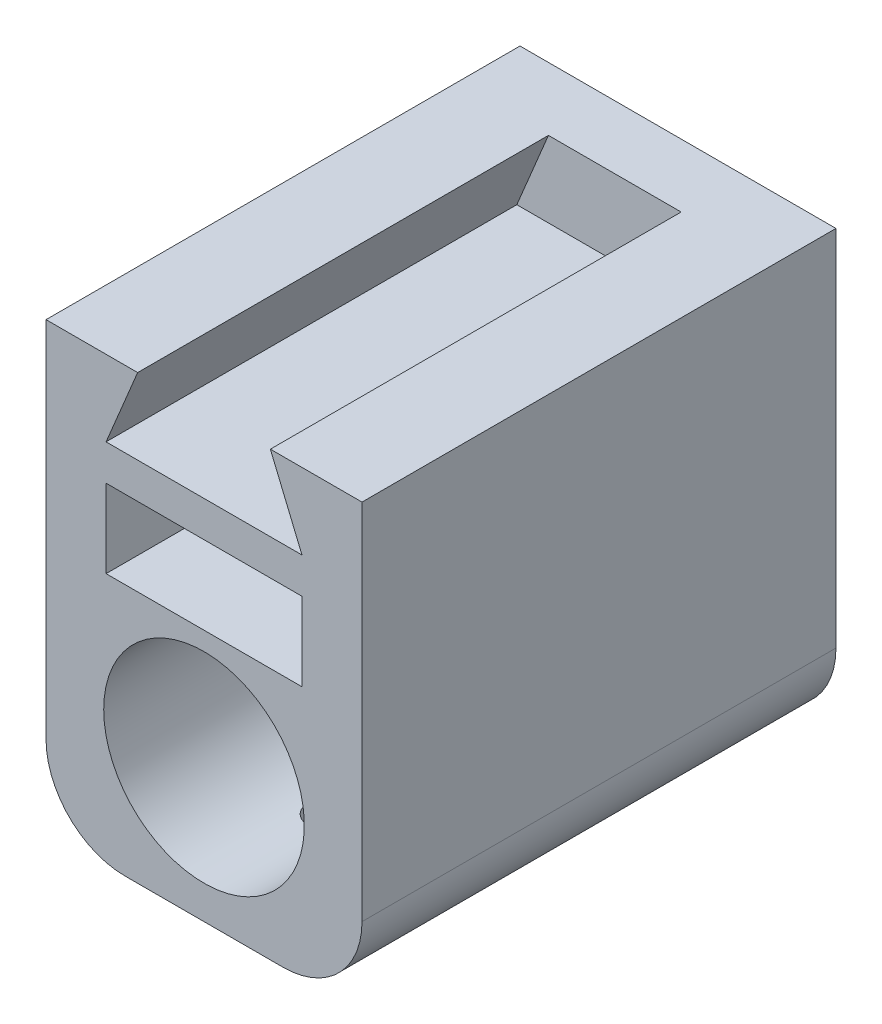
SolidWorks part; units mm, degrees
ref_plane "Plano frontal" through (0, 0, 0) normal (1, 0, 0) x (0, 1, 0)
ref_plane "Plano superior" through (0, 0, 0) normal (0, 0, 1) x (0, 1, 0)
ref_plane "Plano direito" through (0, 0, 0) normal (0, 1, 0) x (-1, 0, 0)
sketch "Esboço1" plane through (0, 0, 0) normal (0, 0, 1) x (0, 1, 0)
  line L16 (3.6178, 6.2) -> (3.6178, -6.2)
  line L17 (3.6178, -6.2) -> (8.4178, -4.2)
  line L19 (8.4178, 4.2) -> (3.6178, 6.2)
  line L20 (8.4178, 4.2) -> (8.4178, 10)
  line L21 (8.4178, 10) -> (-11.1263, 10)
  line L22 (8.4178, -4.2) -> (8.4178, -10)
  line L23 (8.4178, -10) -> (-11.1263, -10)
  line L26 (-11.1263, 10) -> (-19.5822, 10)
  line L27 (-19.5822, 10) -> (-19.5822, -10)
  line L28 (-19.5822, -10) -> (-11.1263, -10)
  line L30 (-3.6057, 6.2) -> (1.3532, 6.2)
  line L31 (-3.6057, 6.2) -> (-3.6057, -6.2)
  line L32 (-3.6057, -6.2) -> (1.3532, -6.2)
  line L33 (1.3532, 6.2) -> (1.3532, -6.2)
  line L34 (-3.6057, 6.2) -> (1.3532, -6.2) construction
  line L35 (-3.6057, -6.2) -> (1.3532, 6.2) construction
  arc A1 (-11.1263, -6.35) -> (-11.1263, 6.35) centre (-11.1263, 0) ccw
  arc A2 (-11.1263, -6.35) -> (-11.1263, 6.35) centre (-11.1263, 0) cw
  point P8 (-4.7763, 0)
  point P10 (3.6178, 0)
  point P17 (-1.1263, 0)
  point P22 (0, 0)
  point P23 (0, 0)
  point P24 (-19.5822, 0)
  dimension "D4" = 19.5441
  dimension "D5" = 12.7
  dimension "D1" = 12.4
  dimension "D2" = 8.4
  dimension "D3" = 4.8
  dimension "D6" = 20
  dimension "D7" = 10
  dimension "D8" = 28
extrude "Ressalto-extrusão1" add sketch "Esboço1" along normal blind 30
sketch "Esboço2" plane through (0, 0, 0) normal (0, 0, 1) x (0, 1, 0)
  line L0 (8.4178, -4.2) -> (3.6178, -6.2) construction
  line L1 (3.6178, 6.2) -> (8.4178, 4.2) construction
  line L2 (3.6178, -6.2) -> (3.6178, 6.2) construction
  line L3 (8.4178, -4.2) -> (3.6178, -6.2)
  line L4 (3.6178, 6.2) -> (8.4178, 4.2)
  line L5 (3.6178, -6.2) -> (3.6178, 6.2)
  line L6 (8.4178, 4.2) -> (8.4178, -4.2)
extrude "Ressalto-extrusão2" add sketch "Esboço2" along normal blind 4
fillet "Filete1" radius 5 2 edges at (10, -19.5822, 15) (-10, -19.5822, 15)
sketch "Esboço3" plane through (0, -19.5822, 0) normal (0, -1, 0) x (1, 0, 0)
  line L0 (0, 22.5) -> (0, 7.5) construction
  line L1 (-10, 0) -> (-10, 30) construction
  circle A0 centre (0, 22.5) radius 1
  circle A1 centre (0, 7.5) radius 1
  point P6 (-10, 15)
  point P7 (0, 15)
  dimension "D1" = 2
  dimension "D2" = 15
extrude "Corte-extrusão1" cut sketch "Esboço3" against normal blind 4
